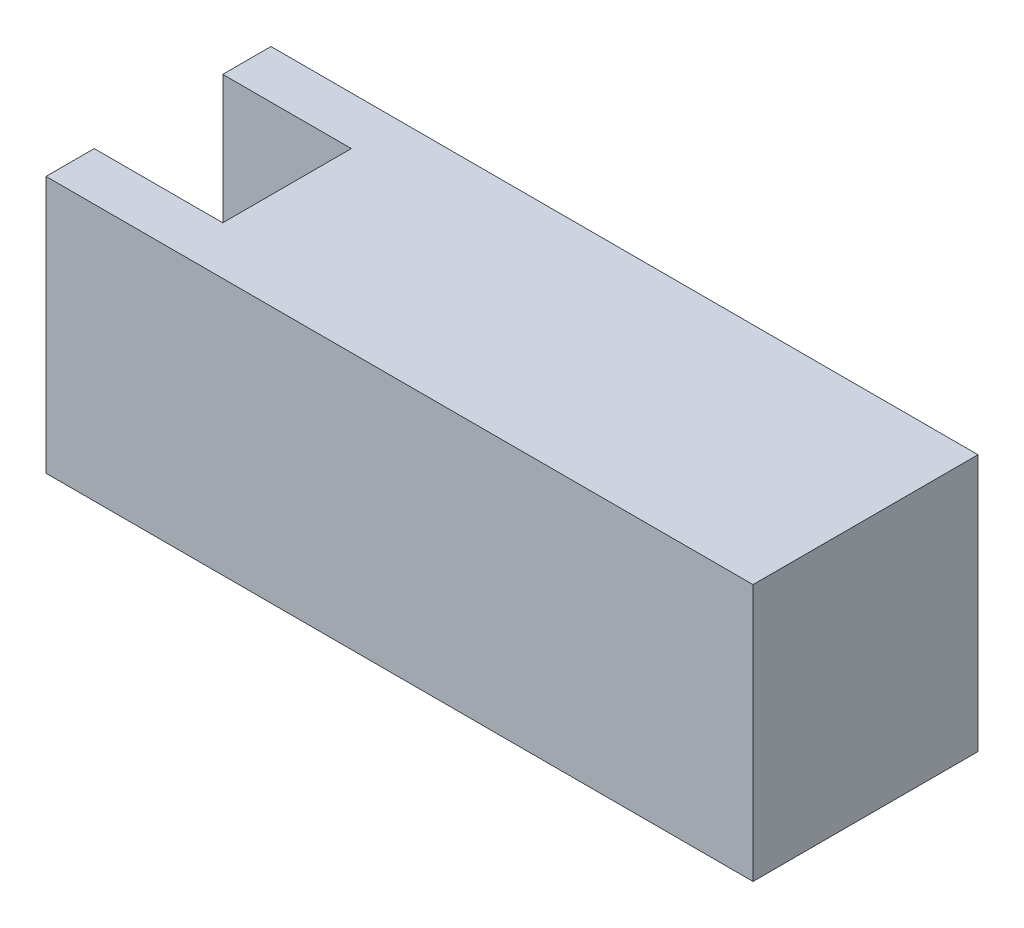
SolidWorks part; units mm, degrees
ref_plane "Front" through (0, 0, 0) normal (0, 0, 1) x (1, 0, 0)
ref_plane "Top" through (0, 0, 0) normal (0, 1, 0) x (1, 0, 0)
ref_plane "Right" through (0, 0, 0) normal (1, 0, 0) x (0, 0, -1)
sketch "Sketch1" plane through (0, 0, 0) normal (0, 0, 1) x (1, 0, 0)
  line L1 (0, 0) -> (-13.97, 0)
  line L2 (0, 0) -> (0, 5.08)
  line L3 (0, 5.08) -> (-13.97, 5.08)
  line L4 (-13.97, 0) -> (-13.97, 5.08)
  dimension "D1" = 13.97
  dimension "D2" = 5.08
extrude "Boss-Extrude1" add sketch "Sketch1" along normal blind 4.445
sketch "Sketch2" plane through (-13.97, 0, 0) normal (-1, 0, 0) x (0, 0, 1)
  line L1 (0.9525, 0) -> (3.4925, 0)
  line L2 (0.9525, 0) -> (0.9525, 5.08)
  line L3 (0.9525, 5.08) -> (3.4925, 5.08)
  line L4 (3.4925, 0) -> (3.4925, 5.08)
  line L5 (0, 1.7396) -> (4.445, 1.7396) construction
  line L6 (0, 5.08) -> (0, 0) construction
  line L7 (4.445, 5.08) -> (4.445, 0) construction
  line L8 (4.445, 5.08) -> (0, 5.08) construction
  line L9 (4.445, 0) -> (0, 0) construction
  point P10 (2.2225, 1.7396)
  point P11 (2.2225, 0)
  point P12 (0, 0)
  dimension "D1" = 2.54
extrude "Cut-Extrude1" cut sketch "Sketch2" against normal blind 2.54
sketch "Sketch3" plane through (0, 0, 0.9525) normal (0, 0, 1) x (1, 0, 0)
  line L0 (-11.43, 5.08) -> (-13.97, 5.08) construction
  line L1 (-11.43, 0) -> (-13.97, 0) construction
  line L2 (-13.97, 5.08) -> (-13.97, 0) construction
  circle A0 centre (-12.7, 3.81) radius 0.4445
  circle A1 centre (-12.7, 1.27) radius 0.4445
  point P8 (0, 0)
  dimension "D1" = 0.889
  dimension ".075" = 1.27
  dimension "D2" = 1.27
  dimension "D3" = 1.27
equation "\"D2@Sketch3\"=\".075@Sketch3\""
